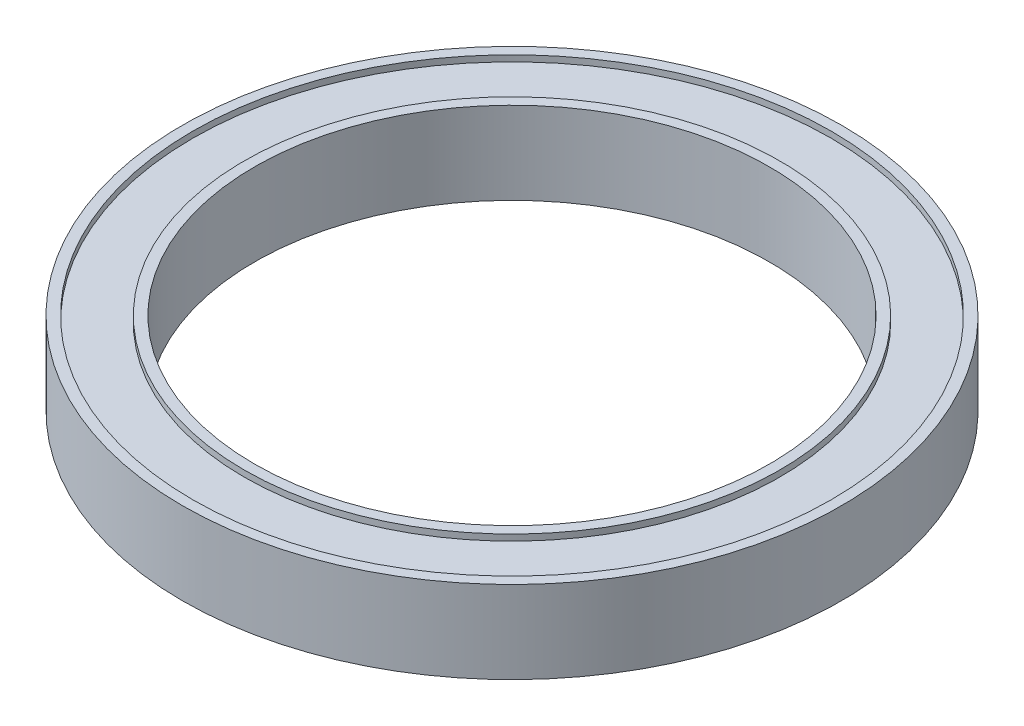
SolidWorks part; units mm, degrees
material "6061 合金"
ref_plane "前视基准面" through (0, 0, 0) normal (0, 0, 1) x (1, 0, 0)
ref_plane "上视基准面" through (0, 0, 0) normal (0, 1, 0) x (1, 0, 0)
ref_plane "右视基准面" through (0, 0, 0) normal (1, 0, 0) x (0, 0, -1)
sketch "草图1" plane through (0, 0, 0) normal (0, 1, 0) x (1, 0, 0)
  circle A0 centre (0, 0) radius 16
  circle A1 centre (0, 0) radius 12.5
  dimension "D1" = 32
  dimension "D2" = 25
extrude "凸台-拉伸1" add sketch "草图1" along normal blind 4
sketch "草图2" plane through (0, 4, 0) normal (0, 1, 0) x (1, 0, 0)
  circle A0 centre (0, 0) radius 15.5
  circle A1 centre (0, 0) radius 13
  circle A2 centre (0, 0) radius 16 construction
  circle A3 centre (0, 0) radius 12.5 construction
  dimension "D1" = 0.5
  dimension "D2" = 0.5
extrude "切除-拉伸1" cut sketch "草图2" against normal blind 0.3
ref_plane "基准面4" through (0, 2, 0) normal (0, 1, 0) x (1, 0, 0)
mirror "镜向1" about plane through (0, 2, 0) normal (0, 1, 0) of "切除-拉伸1"
